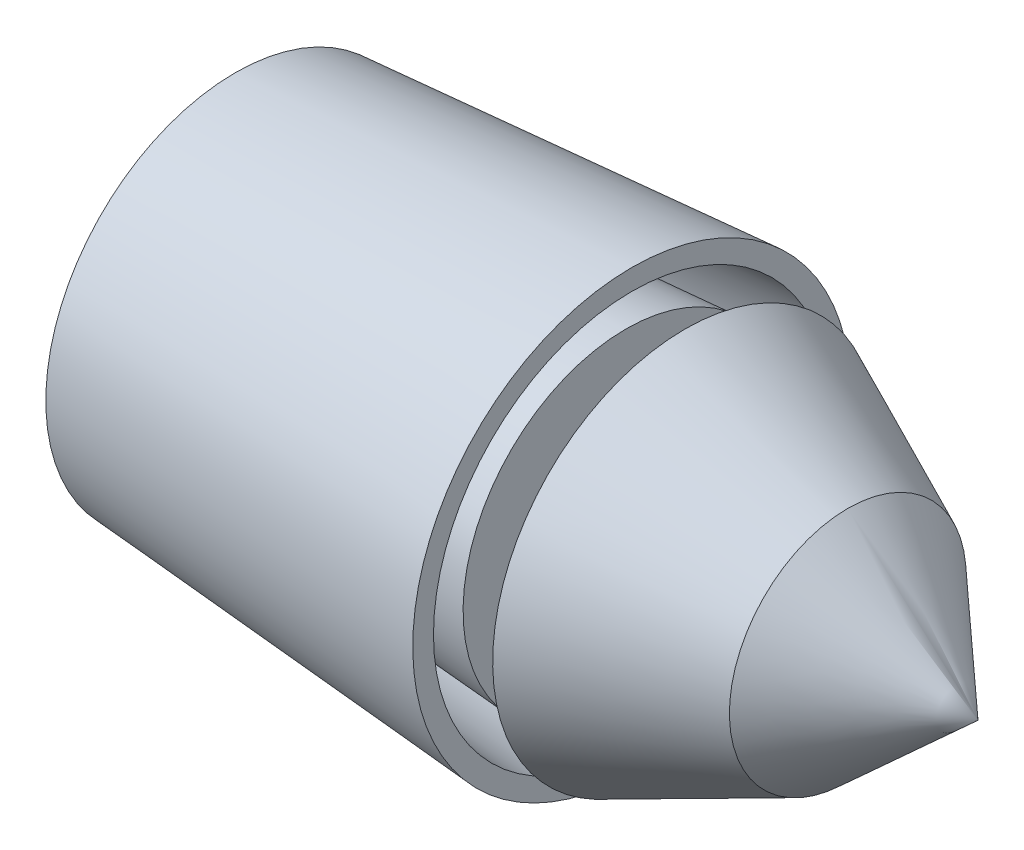
SolidWorks part; units mm, degrees
ref_plane "Front Plane" through (0, 0, 0) normal (0, 0, 1) x (1, 0, 0)
ref_plane "Top Plane" through (0, 0, 0) normal (0, 1, 0) x (1, 0, 0)
ref_plane "Right Plane" through (0, 0, 0) normal (1, 0, 0) x (0, 0, -1)
sketch "Sketch1" plane through (0, 0, 0) normal (0, 0, 1) x (1, 0, 0)
  line L0 (0, 0) -> (7000, 0) construction
  line L1 (4800, 250) -> (4800, 460)
  line L2 (4800, 460) -> (6100, 550)
  line L3 (6100, 550) -> (6100, 250)
  line L4 (6100, 250) -> (4800, 250)
revolve "Revolve1" add sketch "Sketch1" angle 360 about L0
sketch "Sketch2" plane through (0, 0, 0) normal (0, 0, 1) x (1, 0, 0)
  line L0 (0, 0) -> (7000, 0) construction
  line L1 (4780, 580) -> (4780, 640)
  line L2 (4780, 640) -> (6120, 740)
  line L3 (6120, 740) -> (6120, 670)
  line L4 (6120, 670) -> (4780, 580)
revolve "Revolve2" add sketch "Sketch2" angle 360 about L0
sketch "Sketch3" plane through (0, 0, 0) normal (0, 0, 1) x (1, 0, 0)
  line L0 (0, 0) -> (8000, 0) construction
  line L1 (6300, 350) -> (6300, 650)
  line L2 (6300, 650) -> (6850, 400)
  line L3 (6850, 400) -> (7290, 0)
  line L4 (7290, 0) -> (6300, 0)
  line L5 (6300, 0) -> (6300, 350)
revolve "Revolve3" add sketch "Sketch3" angle 360 about L0
